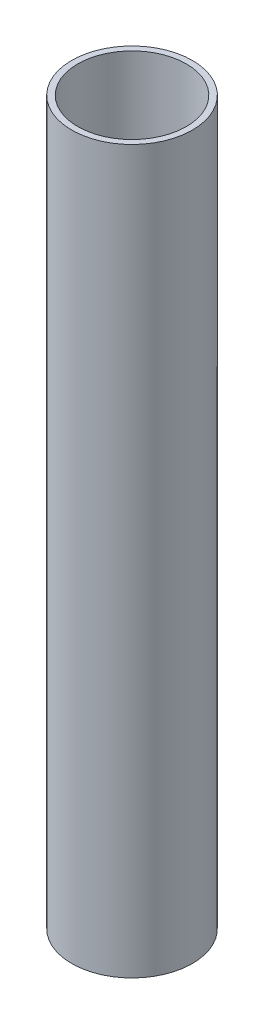
SolidWorks part; units mm, degrees
material "Thornel Mat VMA"
ref_plane "Front Plane" through (0, 0, 0) normal (0, 0, 1) x (1, 0, 0)
ref_plane "Top Plane" through (0, 0, 0) normal (0, 1, 0) x (1, 0, 0)
ref_plane "Right Plane" through (0, 0, 0) normal (1, 0, 0) x (0, 0, -1)
sketch "Sketch1" plane through (0, 0, 0) normal (0, 1, 0) x (1, 0, 0)
  circle A0 centre (0, 0) radius 15
  circle A1 centre (0, 0) radius 13.5
  dimension "D1" = 30
  dimension "D2" = 27
extrude "Boss-Extrude1" add sketch "Sketch1" along normal blind 179.4
